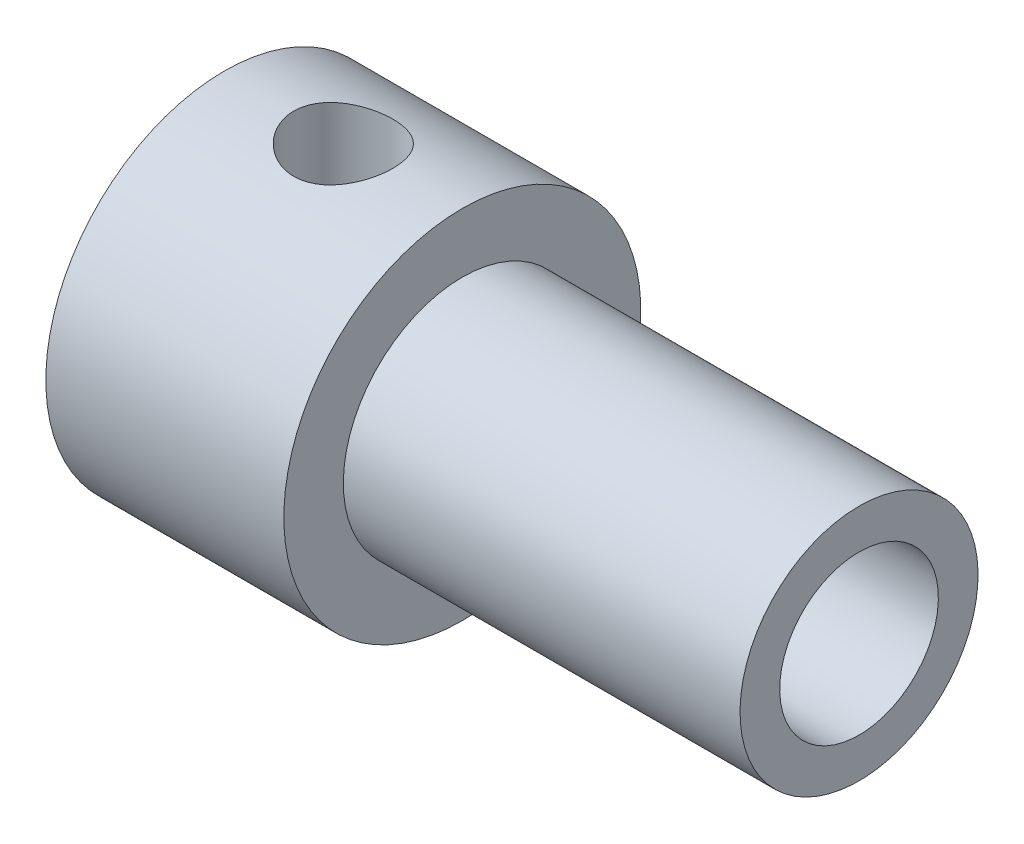
SolidWorks part; units mm, degrees
material "2.1030 (CuSn8P)"
ref_plane "Plan de face" through (0, 0, 0) normal (0, 0, 1) x (1, 0, 0)
ref_plane "Plan de dessus" through (0, 0, 0) normal (0, 1, 0) x (1, 0, 0)
ref_plane "Plan de droite" through (0, 0, 0) normal (1, 0, 0) x (0, 0, -1)
sketch "Esquisse1" plane through (0, 0, 0) normal (0, 0, 1) x (1, 0, 0)
  line L0 (0, 0) -> (0, 1)
  line L1 (0, 1) -> (-10, 1)
  line L2 (-10, 1) -> (-10, 2.5)
  line L3 (-10, 2.5) -> (-16, 2.5)
  line L4 (-16, 2.5) -> (-16, 0)
  line L5 (-16, 0) -> (0, 0)
  line L6 (0, -2) -> (-3.587, -2) construction
  dimension "D1" = 1
  dimension "D2" = 10
  dimension "D3" = 4.5
  dimension "D4" = 2
  dimension "D5" = 6
revolve "Révolution1" add sketch "Esquisse1" angle 360 about L6
ref_plane "Plan1" through (0, 3, 0) normal (0, 1, 0) x (-1, 0, 0)
sketch "Esquisse3" plane through (0, 3, 0) normal (0, 1, 0) x (-1, 0, 0)
  circle A0 centre (13, 0) radius 1.25
  dimension "D1" = 2.5
extrude "Enlèv. mat.-Extru.1" cut sketch "Esquisse3" against normal blind 6
